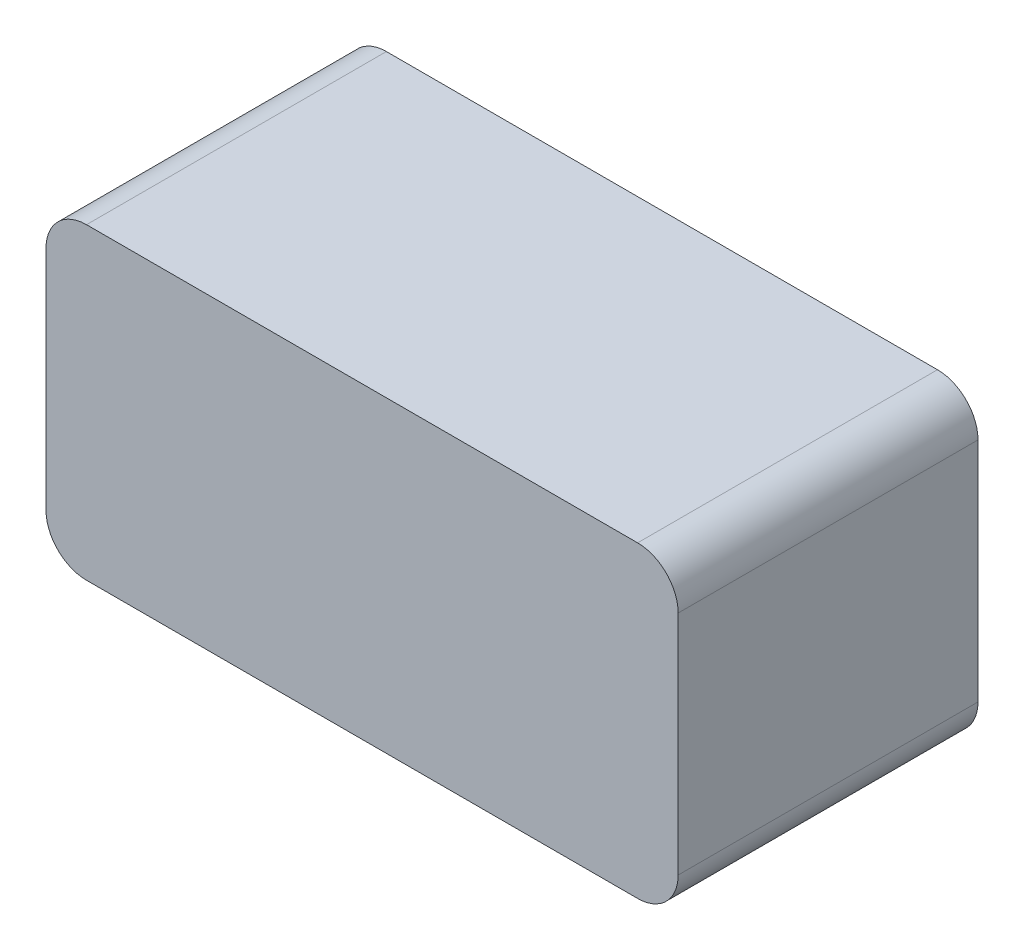
SolidWorks part; units mm, degrees
ref_plane "Front Plane" through (0, 0, 0) normal (0, 0, 1) x (1, 0, 0)
ref_plane "Top Plane" through (0, 0, 0) normal (0, 1, 0) x (1, 0, 0)
ref_plane "Right Plane" through (0, 0, 0) normal (1, 0, 0) x (0, 0, -1)
sketch "Sketch1" plane through (0, 0, 0) normal (0, 1, 0) x (1, 0, 0)
  line L1 (0, 0) -> (78, 0)
  line L2 (0, 0) -> (0, 37)
  line L3 (0, 37) -> (78, 37)
  line L4 (78, 0) -> (78, 37)
  dimension "D1" = 37
  dimension "D2" = 78
extrude "Boss-Extrude1" add sketch "Sketch1" along normal blind 38
fillet "Fillet1" radius 5 4 edges at (78, 0, -18.5) (78, 38, -18.5) (0, 0, -18.5) (0, 38, -18.5)
